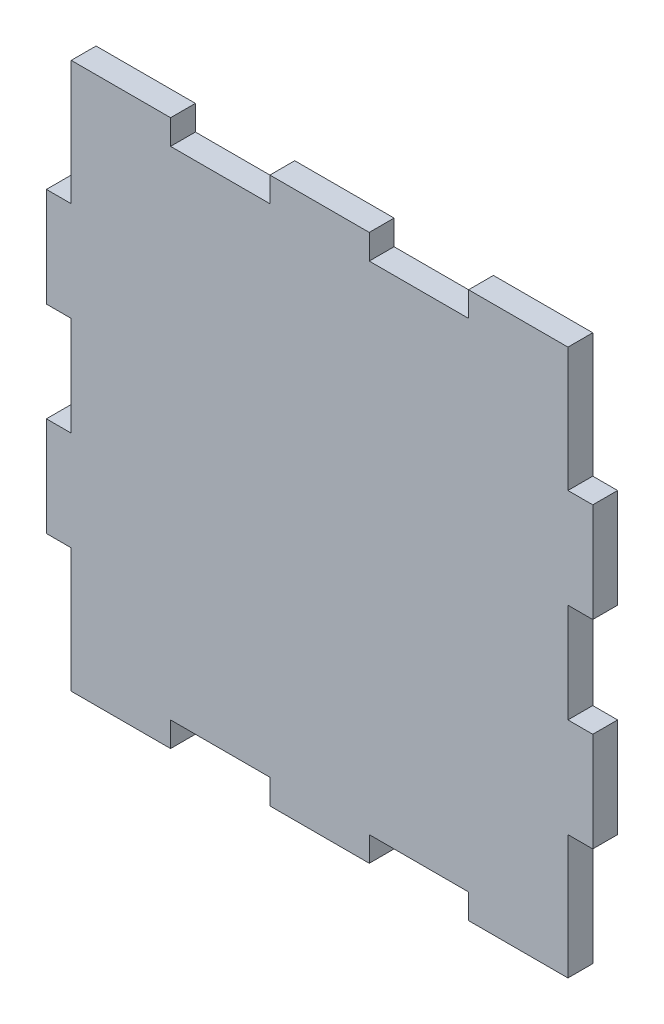
SolidWorks part; units mm, degrees
material "Pinho"
ref_plane "Plano frontal" through (0, 0, 0) normal (0, 0, 1) x (1, 0, 0)
ref_plane "Plano superior" through (0, 0, 0) normal (0, 1, 0) x (1, 0, 0)
ref_plane "Plano direito" through (0, 0, 0) normal (1, 0, 0) x (0, 0, -1)
sketch "Esboço1" plane through (0, 0, 0) normal (0, 0, 1) x (1, 0, 0)
  line L0 (-31.2169, 9.3483) -> (-31.2169, -2.6517)
  line L1 (-19.2169, 33.3483) -> (-7.2169, 33.3483)
  line L2 (-31.2169, 33.3483) -> (-31.2169, 21.3483)
  line L3 (-19.2169, -26.6517) -> (-7.2169, -26.6517)
  line L4 (28.7831, 33.3483) -> (28.7831, 21.3483)
  line L5 (-31.2169, -14.6517) -> (-31.2169, -26.6517)
  line L6 (-31.2169, 9.3483) -> (-34.2169, 9.3483)
  line L7 (4.7831, 33.3483) -> (16.7831, 33.3483)
  line L9 (-31.2169, 21.3483) -> (-34.2169, 21.3483)
  line L10 (-34.2169, 9.3483) -> (-34.2169, 21.3483)
  line L12 (-31.2169, 33.3483) -> (-31.2169, 36.3483)
  line L13 (-34.2169, -14.6517) -> (-31.2169, -14.6517)
  line L14 (-34.2169, -14.6517) -> (-34.2169, -2.6517)
  line L15 (-34.2169, -2.6517) -> (-31.2169, -2.6517)
  line L17 (-31.2169, 36.3483) -> (-19.2169, 36.3483)
  line L18 (-19.2169, 33.3483) -> (-19.2169, 36.3483)
  line L20 (28.7831, 33.3483) -> (28.7831, 36.3483)
  line L21 (28.7831, 36.3483) -> (16.7831, 36.3483)
  line L22 (16.7831, 33.3483) -> (16.7831, 36.3483)
  line L24 (-7.2169, 33.3483) -> (-7.2169, 36.3483)
  line L25 (-7.2169, 36.3483) -> (4.7831, 36.3483)
  line L26 (4.7831, 33.3483) -> (4.7831, 36.3483)
  line L27 (28.7831, -14.6517) -> (28.7831, -26.6517)
  line L28 (28.7831, 9.3483) -> (31.7831, 9.3483)
  line L30 (28.7831, 21.3483) -> (31.7831, 21.3483)
  line L31 (31.7831, 9.3483) -> (31.7831, 21.3483)
  line L32 (4.7831, -26.6517) -> (16.7831, -26.6517)
  line L34 (28.7831, -14.6517) -> (31.7831, -14.6517)
  line L36 (28.7831, -2.6517) -> (31.7831, -2.6517)
  line L37 (31.7831, -14.6517) -> (31.7831, -2.6517)
  line L38 (28.7831, 9.3483) -> (28.7831, -2.6517)
  line L39 (-31.2169, -26.6517) -> (-31.2169, -29.6517)
  line L40 (-31.2169, -29.6517) -> (-19.2169, -29.6517)
  line L41 (-19.2169, -26.6517) -> (-19.2169, -29.6517)
  line L43 (28.7831, -26.6517) -> (28.7831, -29.6517)
  line L44 (28.7831, -29.6517) -> (16.7831, -29.6517)
  line L45 (16.7831, -26.6517) -> (16.7831, -29.6517)
  line L47 (-7.2169, -26.6517) -> (-7.2169, -29.6517)
  line L48 (-7.2169, -29.6517) -> (4.7831, -29.6517)
  line L49 (4.7831, -26.6517) -> (4.7831, -29.6517)
  point P0 (0, 0)
  point P10 (0, 0)
  point P15 (0, 0)
  point P22 (0, 0)
  point P46 (0, 0)
  point P48 (0, 0)
  dimension "D1" = 60
  dimension "D2" = 60
  dimension "D3" = 12
  dimension "D4" = 12
  dimension "D5" = 12
  dimension "D6" = 12
  dimension "D7" = 12
  dimension "D8" = 12
  dimension "D9" = 12
  dimension "D10" = 12
  dimension "D11" = 12
  dimension "D12" = 12
  dimension "D13" = 12
  dimension "D14" = 12
  dimension "D15" = 12
  dimension "D16" = 12
  dimension "D17" = 3
  dimension "D18" = 3
  dimension "D19" = 3
  dimension "D20" = 3
  dimension "D21" = 3
  dimension "D22" = 3
  dimension "D23" = 3
  dimension "D24" = 3
  dimension "D25" = 3
  dimension "D26" = 3
  dimension "D27" = 3
  dimension "D28" = 3
  dimension "D29" = 3
  dimension "D30" = 12
  dimension "D31" = 3
extrude "Ressalto-extrusão1" add sketch "Esboço1" along normal blind 3
